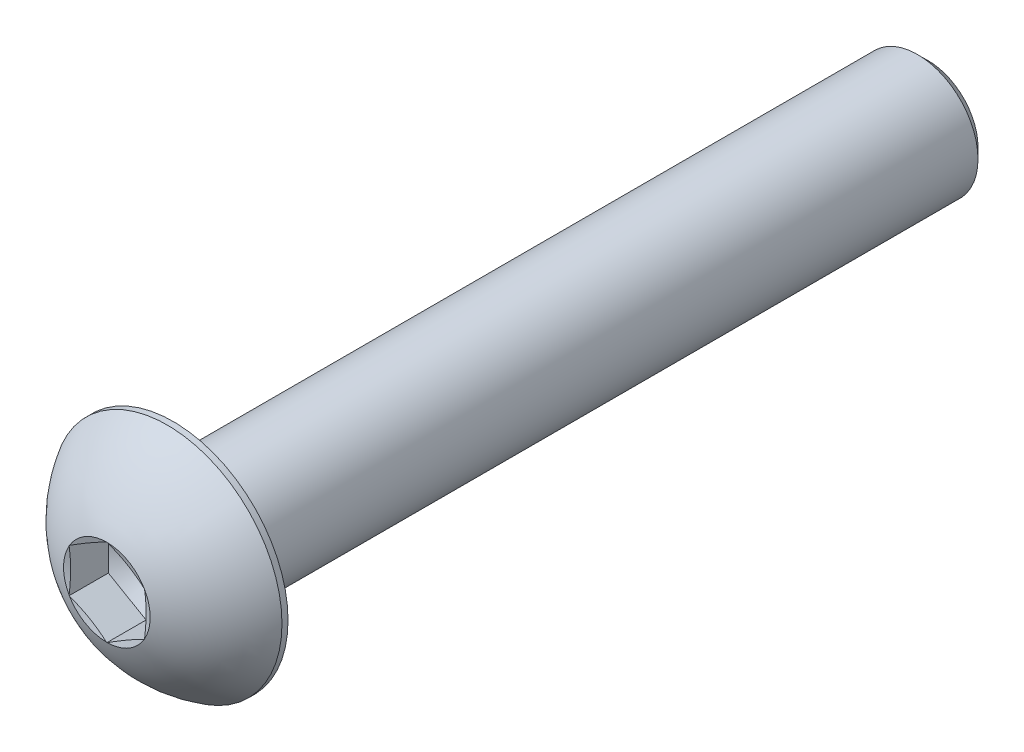
SolidWorks part; units mm, degrees
ref_plane "Front Plane" through (0, 0, 0) normal (0, 0, 1) x (1, 0, 0)
ref_plane "Top Plane" through (0, 0, 0) normal (0, 1, 0) x (1, 0, 0)
ref_plane "Right Plane" through (0, 0, 0) normal (1, 0, 0) x (0, 0, -1)
sketch "Sketch1" plane through (0, 0, 0) normal (1, 0, 0) x (0, 0, -1)
  line L0 (0, 0) -> (31.0773, 0) construction
  line L1 (0, 0) -> (0, 1.435)
  line L3 (26.85, 2) -> (2.4, 2)
  line L4 (2.2, 2.2) -> (2.2, 3.8)
  line L7 (27.2, 0) -> (0, 0)
  line L8 (26.85, 2) -> (27.2, 1.65)
  line L9 (27.2, 1.65) -> (27.2, 0)
  line L10 (2.2, 3.8) -> (2, 3.8)
  arc A0 (2.4, 2) -> (2.2, 2.2) centre (2.4, 2.2) cw
  arc A6 (2, 3.8) -> (0, 1.435) centre (4.3074, -0.1794) ccw
  dimension "Rs" = 0.2
  dimension "Rf" = 4.6
  dimension "D3" = 0.2
  dimension "Hole1" = 4
  dimension "Hole2" = 3.3
  dimension "D12" = 45
  dimension "Length" = 25
  dimension "K" = 2.2
  dimension "DL" = 2.87
  dimension "Dk" = 7.6
revolve "Revolve1" add sketch "Sketch1" angle 360 about L0
cosmetic thread "Cosmetic Thread1" parameters "D1"=23.6, "D2"=4
sketch "Sketch2" plane through (0, 0, 0) normal (0, 0, 1) x (1, 0, 0)
  line L0 (0, 0) -> (0, 1.4434) construction
  line L7 (0, -1.4434) -> (1.25, -0.7217)
  line L14 (1.25, -0.7217) -> (1.25, 0.7217)
  line L15 (1.25, 0.7217) -> (0, 1.4434)
  line L16 (0, 1.4434) -> (-1.25, 0.7217)
  line L17 (-1.25, 0.7217) -> (-1.25, -0.7217)
  line L18 (-1.25, -0.7217) -> (0, -1.4434)
  circle A1 centre (0, 0) radius 1.25 construction
  dimension "D1" = 2.5
extrude "Cut-Extrude2" cut sketch "Sketch2" against normal blind 1.3
sketch "Sketch5" plane through (0, 0, 0) normal (1, 0, 0) x (0, 0, -1)
  line L3 (0.0496, -1.25) -> (0, -1.435)
  line L4 (0, 0) -> (27.2, 0) construction
  line L5 (27.2, -1.65) -> (27.2, 1.65) construction
  line L6 (0.0496, -1.25) -> (0, -1.25)
  line L7 (0, -1.25) -> (0, -1.435)
  dimension "D1" = 15
  dimension "D2" = 2.5
  dimension "D3" = 2.87
revolve "Cut-Revolve3" cut sketch "Sketch5" angle 360 about L4
sketch "Sketch4" plane through (0, 0, 0) normal (1, 0, 0) x (0, 0, -1)
  line L0 (1.3, 0) -> (31.2977, 0) construction
  line L1 (1.3, 0) -> (1.3, -1.4434)
  line L5 (1.3, -1.4434) -> (2.1333, 0)
  line L7 (2.1333, 0) -> (1.3, 0)
  dimension "D1" = 60
revolve "Cut-Revolve2" cut sketch "Sketch4" angle 360 about L0
